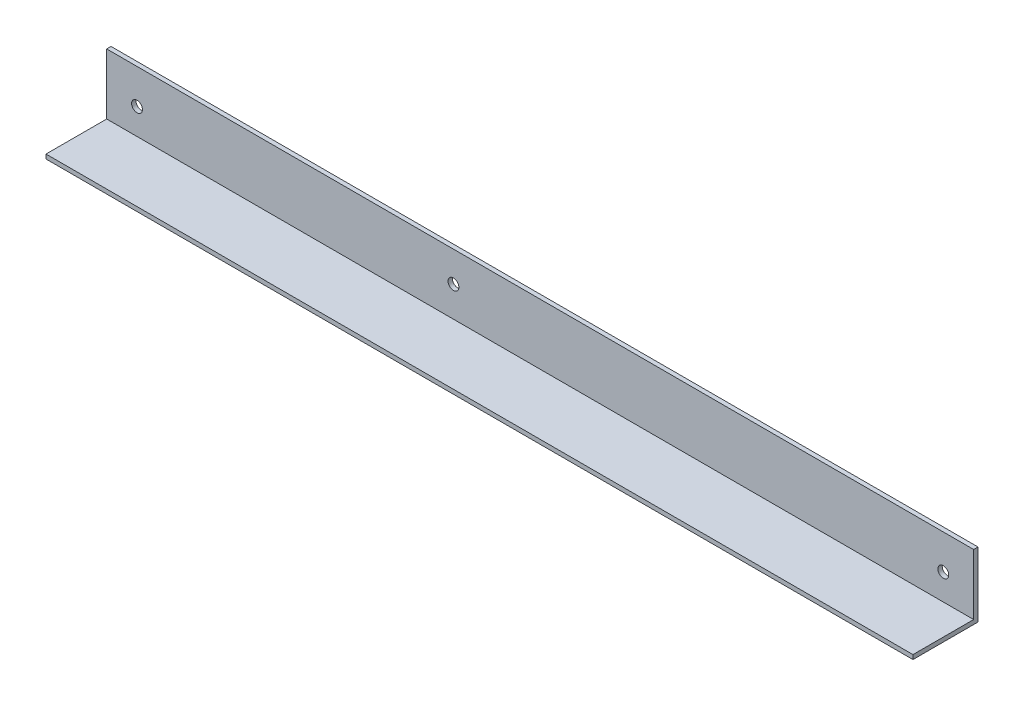
SolidWorks part; units mm, degrees
ref_plane "正面" through (0, 0, 0) normal (0, 0, 1) x (1, 0, 0)
ref_plane "平面" through (0, 0, 0) normal (0, 1, 0) x (1, 0, 0)
ref_plane "右側面" through (0, 0, 0) normal (1, 0, 0) x (0, 0, -1)
sketch "ｽｹｯﾁ1" plane through (0, 0, 0) normal (0, 0, 1) x (1, 0, 0)
  line L1 (0, 0) -> (200, 0)
  line L2 (0, 0) -> (0, 15)
  line L3 (0, 15) -> (200, 15)
  line L4 (200, 0) -> (200, 15)
  dimension "D1" = 200
  dimension "D2" = 15
extrude "ﾎﾞｽ - 押し出し1" add sketch "ｽｹｯﾁ1" along normal blind 1
sketch "ｽｹｯﾁ2" plane through (0, 0, 1) normal (0, 0, 1) x (1, 0, 0)
  line L1 (0, 0) -> (200, 0)
  line L2 (0, 0) -> (0, 1)
  line L3 (0, 1) -> (200, 1)
  line L4 (200, 0) -> (200, 1)
  dimension "D1" = 200
  dimension "D2" = 1
extrude "ﾎﾞｽ - 押し出し2" add sketch "ｽｹｯﾁ2" along normal blind 14
hole_wizard "M3x0.5 ねじ穴1" positions "ｽｹｯﾁ5" profile "ｽｹｯﾁ6" tap size "M3x0.5" standard "JIS" end condition through all
sketch "ｽｹｯﾁ5" plane through (0, 0, 0) normal (0, 0, -1) x (-1, 0, 0)
  line L0 (-200, 0) -> (-200, 15) construction
  line L1 (0, 0) -> (-200, 0) construction
  point P0 (-193, 7)
  dimension "D1" = 7
  dimension "D2" = 7
sketch "ｽｹｯﾁ6" plane through (193, 7, 0) normal (1, 0, 0) x (0, 1, 0)
  line L0 (0, 0) -> (0, 15)
  line L1 (0, 15) -> (1.25, 15)
  line L2 (1.25, 15) -> (1.25, 0)
  line L5 (1.25, 0) -> (0, 0)
  line L11 (0, -6.35) -> (0, 107.95) construction
  dimension "次ｻｰﾌｪｽまでのねじ下穴ﾄﾞﾘﾙ直径" = 2.5
  dimension "次ｻｰﾌｪｽまでのねじ下穴ﾄﾞﾘﾙの深さ" = 15
cosmetic thread "穴のねじ山3" parameters "D2"=3
hole_wizard "M3x0.5 ねじ穴2" positions "ｽｹｯﾁ7" profile "ｽｹｯﾁ8" tap size "M3x0.5" standard "JIS" end condition through all
sketch "ｽｹｯﾁ7" plane through (0, 0, 1) normal (0, 0, 1) x (1, 0, 0)
  line L0 (200, 15) -> (0, 15) construction
  line L1 (200, 1) -> (200, 15) construction
  point P0 (80, 8)
  point P7 (200, 8)
  dimension "D1" = 7
  dimension "D2" = 120
sketch "ｽｹｯﾁ8" plane through (80, 8, 1) normal (1, 0, 0) x (0, -1, 0)
  line L0 (0, 0) -> (0, 1)
  line L1 (0, 1) -> (1.25, 1)
  line L2 (1.25, 1) -> (1.25, 0)
  line L5 (1.25, 0) -> (0, 0)
  line L11 (0, -6.35) -> (0, 107.95) construction
  dimension "次ｻｰﾌｪｽまでのねじ下穴ﾄﾞﾘﾙ直径" = 2.5
  dimension "次ｻｰﾌｪｽまでのねじ下穴ﾄﾞﾘﾙの深さ" = 1
cosmetic thread "穴のねじ山4" parameters "D2"=3
hole_wizard "M3x0.5 ねじ穴3" positions "ｽｹｯﾁ9" profile "ｽｹｯﾁ10" tap size "M3x0.5" standard "JIS" end condition through all
sketch "ｽｹｯﾁ9" plane through (0, 0, 0) normal (0, 0, -1) x (-1, 0, 0)
  line L0 (0, 15) -> (0, 0) construction
  line L1 (0, 0) -> (-200, 0) construction
  point P0 (-7, 7)
  dimension "D1" = 7
  dimension "D2" = 7
sketch "ｽｹｯﾁ10" plane through (7, 7, 0) normal (1, 0, 0) x (0, 1, 0)
  line L0 (0, 0) -> (0, 15)
  line L1 (0, 15) -> (1.25, 15)
  line L2 (1.25, 15) -> (1.25, 0)
  line L5 (1.25, 0) -> (0, 0)
  line L11 (0, -6.35) -> (0, 107.95) construction
  dimension "次ｻｰﾌｪｽまでのねじ下穴ﾄﾞﾘﾙ直径" = 2.5
  dimension "次ｻｰﾌｪｽまでのねじ下穴ﾄﾞﾘﾙの深さ" = 15
cosmetic thread "穴のねじ山5" parameters "D2"=3
